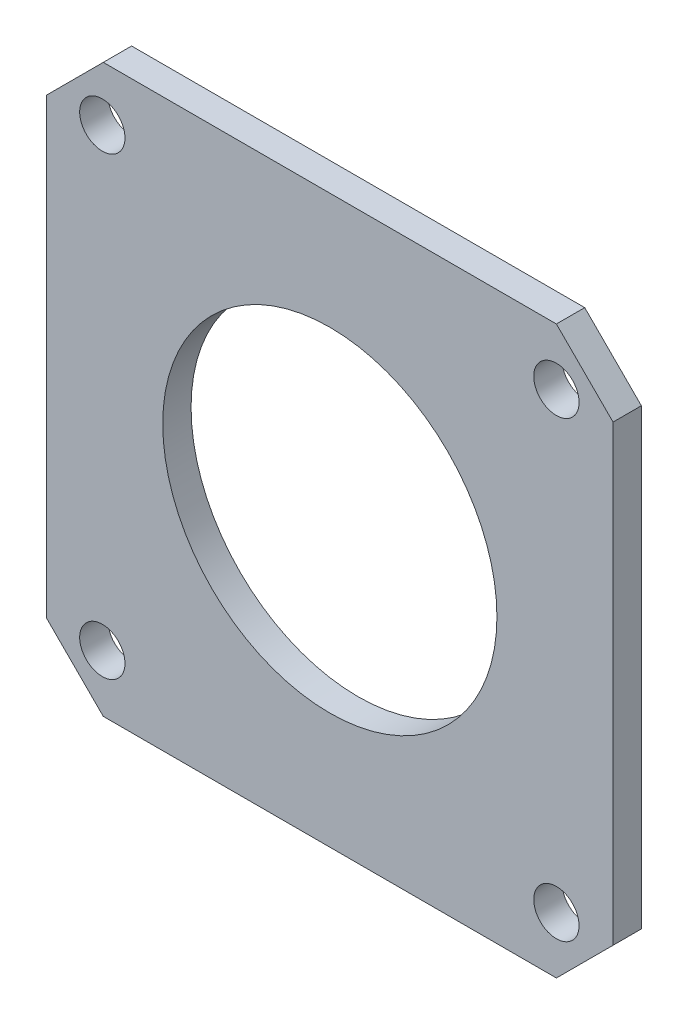
SolidWorks part; units mm, degrees
ref_plane "Front Plane" through (0, 0, 0) normal (0, 0, 1) x (1, 0, 0)
ref_plane "Top Plane" through (0, 0, 0) normal (0, 1, 0) x (1, 0, 0)
ref_plane "Right Plane" through (0, 0, 0) normal (1, 0, 0) x (0, 0, -1)
sketch "Sketch3" plane through (0, 0, 0) normal (0, 0, 1) x (1, 0, 0)
  line L0 (90, 100) -> (90, 0) construction
  line L1 (10, 0) -> (90, 0)
  line L2 (0, 10) -> (0, 90)
  line L3 (10, 100) -> (90, 100)
  line L4 (100, 10) -> (100, 90)
  line L5 (9.8322, 100) -> (9.8322, 0) construction
  line L6 (0, 90.3357) -> (100, 90.3357) construction
  line L7 (0, 10) -> (100, 10) construction
  line L8 (0, 90) -> (10, 100)
  line L9 (90, 100) -> (100, 90)
  line L10 (90, 0) -> (100, 10)
  line L11 (0, 10) -> (10, 0)
  circle A0 centre (90, 90) radius 4
  circle A1 centre (9.8322, 90.3357) radius 4
  circle A2 centre (9.8322, 10) radius 4
  circle A3 centre (90, 10) radius 4
  point P0 (0, 0)
  point P1 (100, 100)
  point P2 (0, 100)
  point P3 (100, 0)
  dimension "D1" = 100
  dimension "D2" = 100
  dimension "D10" = 10
  dimension "D11" = 10
extrude "Boss-Extrude2" add sketch "Sketch3" against normal blind 5
sketch "Sketch5" plane through (0, 0, 0) normal (0, 0, 1) x (1, 0, 0)
  line L0 (50, 100) -> (50, 0)
  line L1 (90, 100) -> (10, 100) construction
  line L2 (10, 0) -> (90, 0) construction
  line L3 (100, 50) -> (0, 50)
  line L4 (100, 10) -> (100, 90) construction
  line L5 (0, 90) -> (0, 10) construction
  circle A0 centre (50, 50) radius 29.5
extrude "Cut-Extrude1" cut sketch "Sketch5" against normal blind 24 and the other way blind 4 contours L0 A0 L3 | L3 A0 L0
